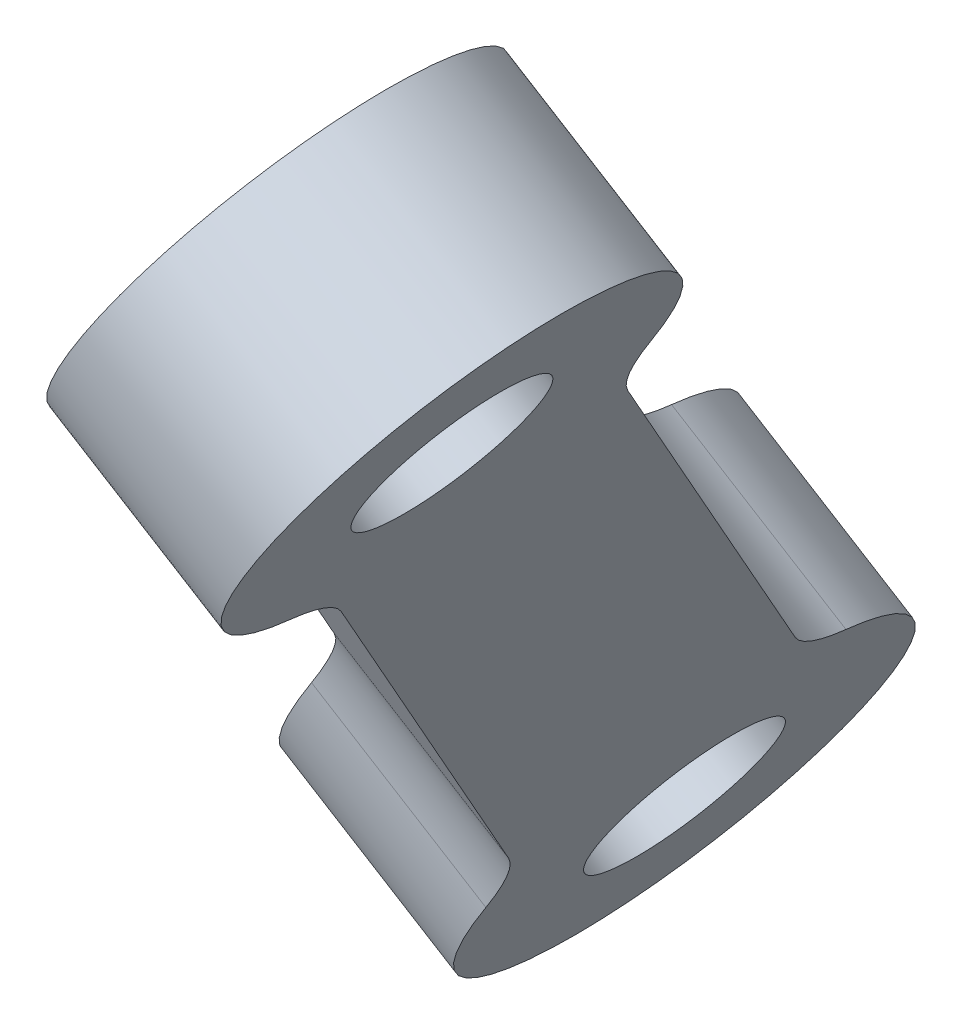
SolidWorks part; units mm, degrees
ref_plane "Front Plane" through (0, 0, 0) normal (0, 0, 1) x (1, 0, 0)
ref_plane "Top Plane" through (0, 0, 0) normal (0, 1, 0) x (1, 0, 0)
ref_plane "Right Plane" through (0, 0, 0) normal (1, 0, 0) x (0, 0, -1)
ref_plane "Plane1" through (-205.2469, 127.5291, 0.6038) normal (-0.8494, 0.5278, 0.0025) x (-0.5278, -0.8494, 0)
sketch "Sketch1" plane through (-205.2469, 127.5291, 0.6038) normal (-0.8494, 0.5278, 0.0025) x (-0.5278, -0.8494, 0)
  line L0 (-131.2993, 83.4276) -> (-113.0749, 70.5073)
  line L1 (-110.1832, 74.5862) -> (-128.4076, 87.5065)
  circle A0 centre (-133.3859, 87.9714) radius 1.75
  circle A1 centre (-108.0966, 70.0424) radius 1.75
  arc A2 (-129.5497, 89.1043) -> (-133.185, 83.9765) centre (-133.3859, 87.9714) ccw
  arc A3 (-133.185, 83.9765) -> (-131.2993, 83.4276) centre (-133.0344, 80.9803) cw
  arc A4 (-113.0749, 70.5073) -> (-111.9328, 68.9095) centre (-114.81, 68.0599) cw
  arc A5 (-111.9328, 68.9095) -> (-108.2974, 74.0373) centre (-108.0966, 70.0424) ccw
  arc A6 (-108.2974, 74.0373) -> (-110.1832, 74.5862) centre (-108.4481, 77.0335) cw
  arc A7 (-128.4076, 87.5065) -> (-129.5497, 89.1043) centre (-126.6725, 89.9539) cw
extrude "Boss-Extrude1" add sketch "Sketch1" against normal blind 4
